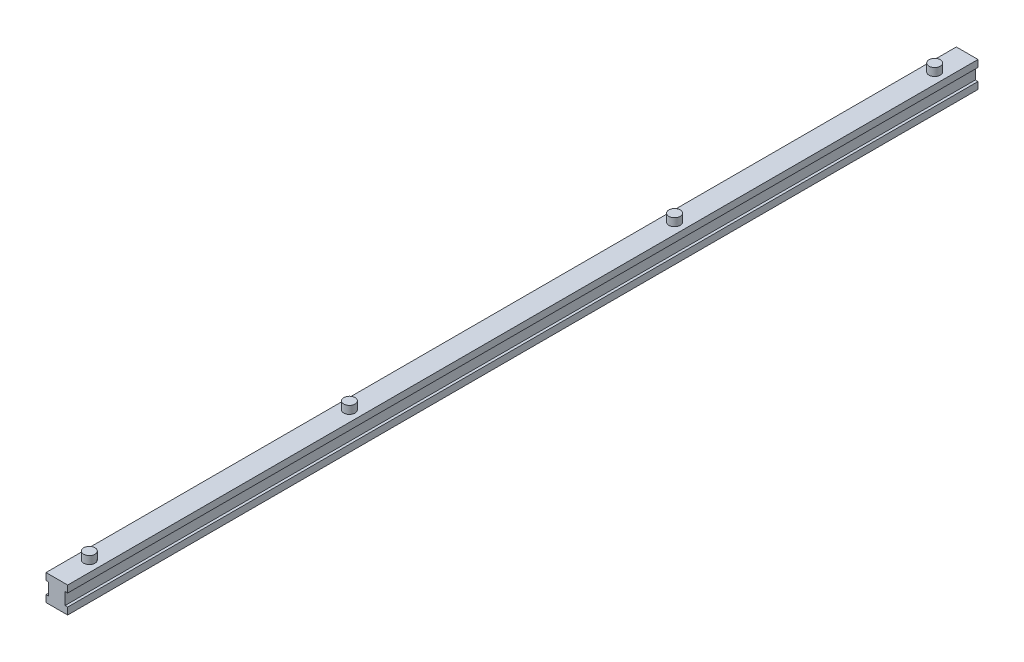
SolidWorks part; units mm, degrees
ref_plane "Front Plane" through (0, 0, 0) normal (0, 0, 1) x (1, 0, 0)
ref_plane "Top Plane" through (0, 0, 0) normal (0, 1, 0) x (1, 0, 0)
ref_plane "Right Plane" through (0, 0, 0) normal (1, 0, 0) x (0, 0, -1)
sketch "Sketch1" plane through (0, 0, 0) normal (0, 1, 0) x (1, 0, 0)
  line L1 (1.25, -52.5) -> (-1.25, -52.5)
  line L2 (1.25, -52.5) -> (1.25, 52.5)
  line L3 (1.25, 52.5) -> (-1.25, 52.5)
  line L4 (-1.25, -52.5) -> (-1.25, 52.5)
  line L5 (1.25, -52.5) -> (-1.25, 52.5) construction
  line L6 (1.25, 52.5) -> (-1.25, -52.5) construction
  point P0 (0, 0)
  dimension "D1" = 2.5
  dimension "D2" = 105
extrude "Boss-Extrude1" add sketch "Sketch1" along normal blind 0.8
sketch "Sketch2" plane through (0, 0.8, 0) normal (0, 1, 0) x (1, 0, 0)
  line L0 (1.25, 52.5) -> (-1.25, 52.5) construction
  line L1 (0.95, -52.5) -> (-0.95, -52.5)
  line L2 (0.95, -52.5) -> (0.95, 52.5)
  line L3 (0.95, 52.5) -> (-0.95, 52.5)
  line L4 (-0.95, -52.5) -> (-0.95, 52.5)
  line L5 (0.95, -52.5) -> (-0.95, 52.5) construction
  line L6 (0.95, 52.5) -> (-0.95, -52.5) construction
  line L7 (-1.25, 52.5) -> (-1.25, -52.5) construction
  point P0 (0, 0)
  dimension "D1" = 0.3
extrude "Boss-Extrude2" add sketch "Sketch2" along normal blind 1.4
sketch "Sketch3" plane through (0, 2.2, 0) normal (0, 1, 0) x (1, 0, 0)
  line L4 (-1.25, 52.5) -> (-1.25, -52.5)
  line L5 (1.25, 52.5) -> (-1.25, 52.5)
  line L6 (1.25, -52.5) -> (1.25, 52.5)
  line L7 (-1.25, -52.5) -> (1.25, -52.5)
  line L8 (-1.25, 52.5) -> (-1.25, -52.5)
  line L9 (1.25, 52.5) -> (-1.25, 52.5)
  line L10 (1.25, -52.5) -> (1.25, 52.5)
  line L11 (-1.25, -52.5) -> (1.25, -52.5)
  dimension "D1" = 0
extrude "Boss-Extrude3" add sketch "Sketch3" along normal blind 0.8
sketch "Sketch4" plane through (0, 3, 0) normal (0, 1, 0) x (1, 0, 0)
  line L0 (0, -48.75) -> (0, 48.75) construction
  circle A0 centre (0, 18.75) radius 0.65
  circle A1 centre (0, -18.75) radius 0.65
  circle A2 centre (0, 48.75) radius 0.65
  circle A3 centre (0, -48.75) radius 0.65
  point P2 (0, 0)
  point P10 (1.25, 48.75)
  point P11 (-1.25, 48.75)
  dimension "D4" = 1.3
  dimension "D1" = 37.5
  dimension "D2" = 30
  dimension "D3" = 30
extrude "Boss-Extrude4" add sketch "Sketch4" along normal blind 0.9
